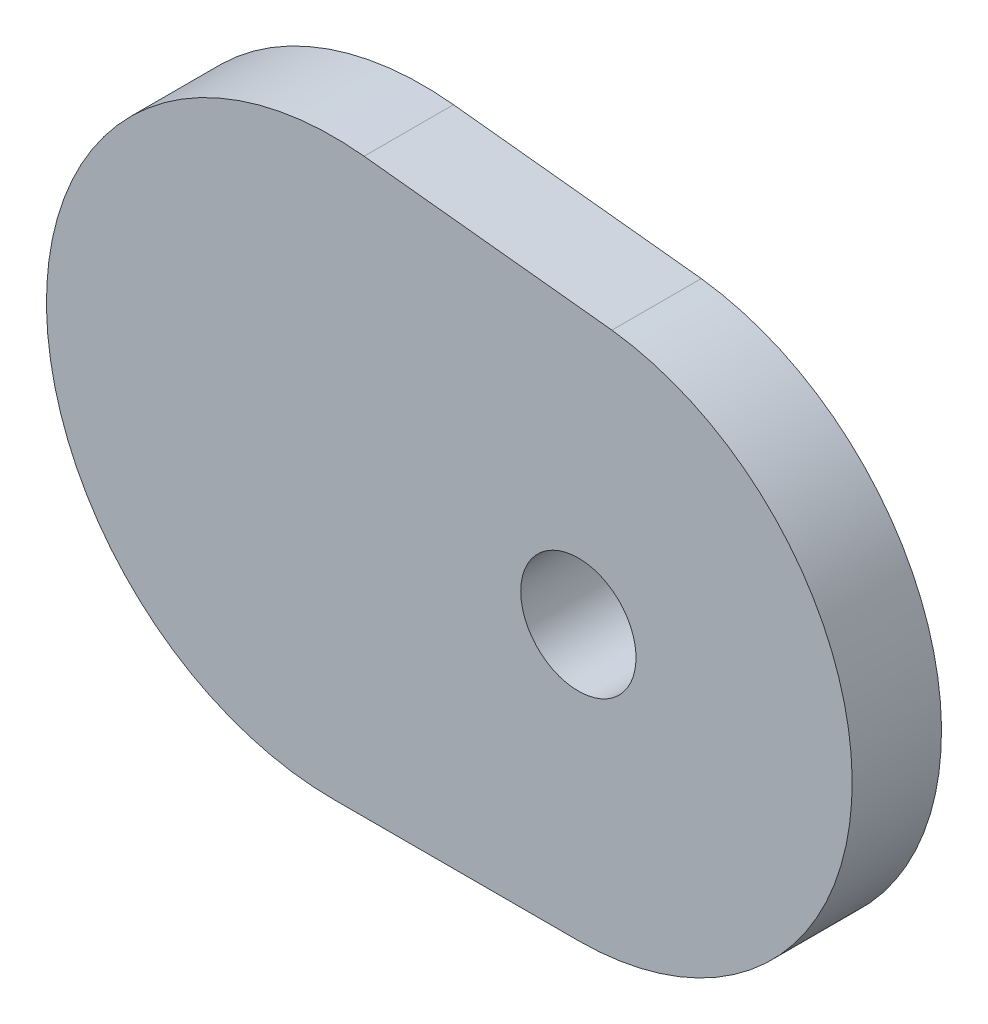
SolidWorks part; units mm, degrees
ref_plane "Front Plane" through (0, 0, 0) normal (0, 0, 1) x (1, 0, 0)
ref_plane "Top Plane" through (0, 0, 0) normal (0, 1, 0) x (1, 0, 0)
ref_plane "Right Plane" through (0, 0, 0) normal (1, 0, 0) x (0, 0, -1)
sketch "Sketch1" plane through (0, 0, 0) normal (0, 0, 1) x (1, 0, 0)
  line L0 (-17, -19) -> (0, -19)
  line L1 (2.3283, 18.8568) -> (-14.8683, 20.7085)
  circle A0 centre (0, 0) radius 4
  arc A1 (-14.8683, 20.7085) -> (-17, -19) centre (-17, 0.9115) ccw
  arc A3 (0, -19) -> (2.3283, 18.8568) centre (0, 0) ccw
  arc A6 (2.3283, 18.8568) -> (-262.4502, -13.0125) centre (-65.6814, -531.9605) ccw construction
  dimension "D1" = 8
  dimension "D2" = 19
  dimension "D3" = 17
extrude "Boss-Extrude1" add sketch "Sketch1" along normal blind 6.2
